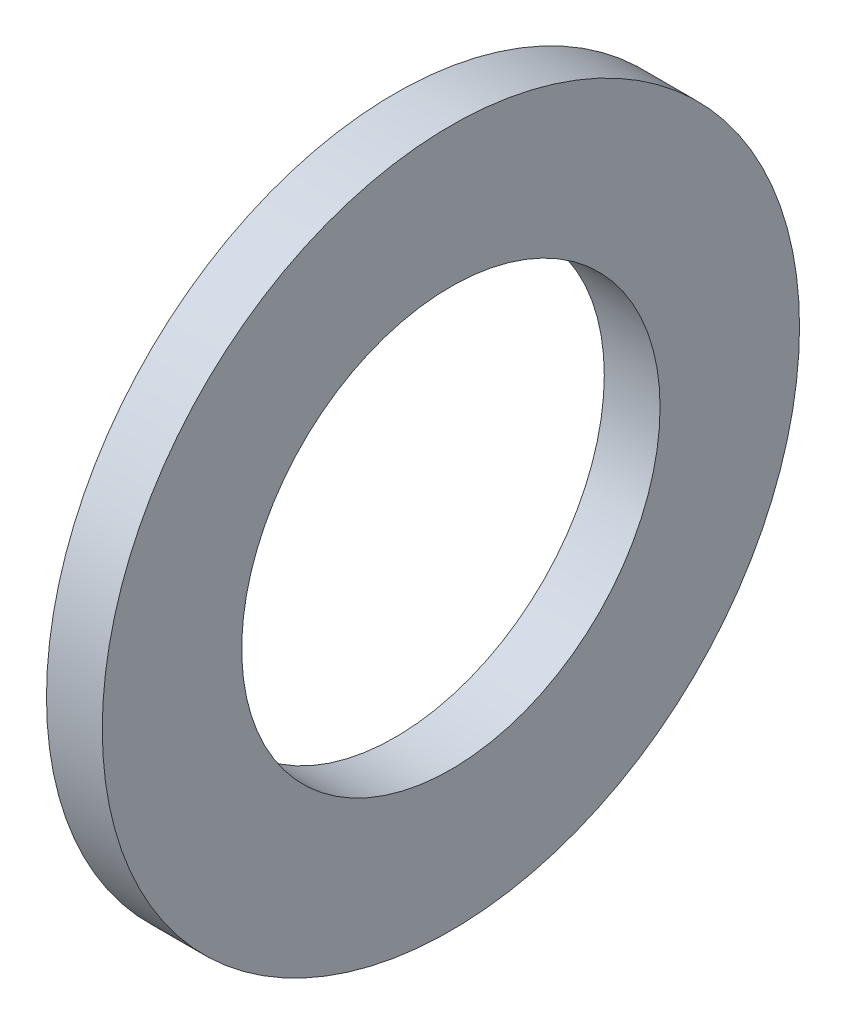
SolidWorks part; units mm, degrees
ref_plane "Front Plane" through (0, 0, 0) normal (0, 0, 1) x (1, 0, 0)
ref_plane "Top Plane" through (0, 0, 0) normal (0, 1, 0) x (1, 0, 0)
ref_plane "Right Plane" through (0, 0, 0) normal (1, 0, 0) x (0, 0, -1)
sketch "Sketch1" plane through (0, 0, 0) normal (1, 0, 0) x (0, 0, -1)
  circle A2 centre (0, 0) radius 12.5
  circle A3 centre (0, 0) radius 7.5
  dimension "D1" = 25
  dimension "D2" = 5
extrude "Boss-Extrude1" add sketch "Sketch1" along normal mid plane 2
